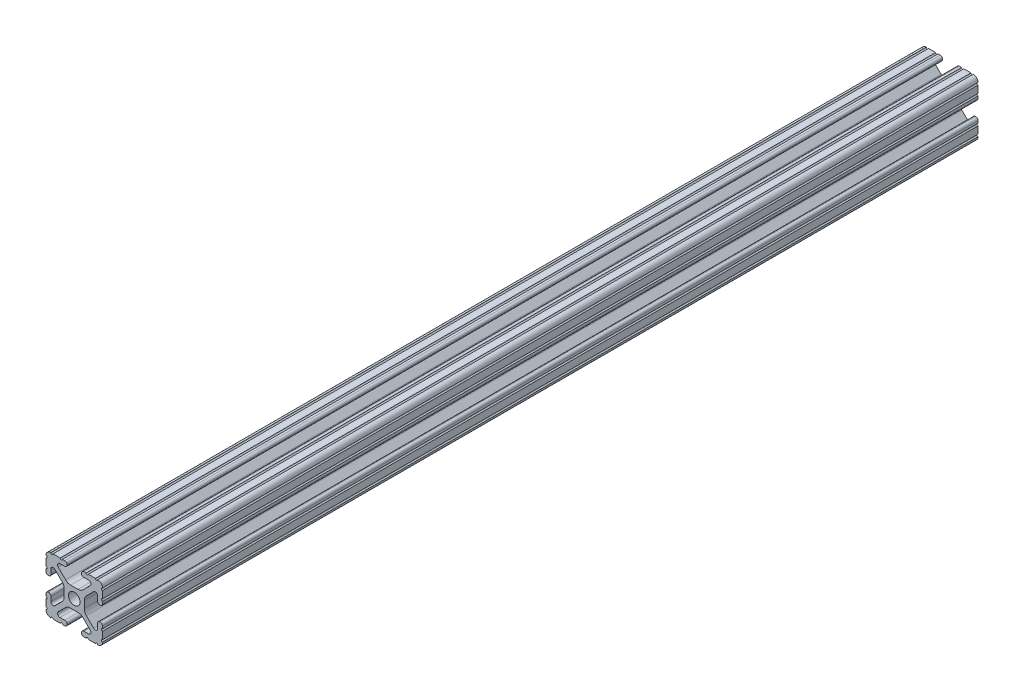
SolidWorks part; units mm, degrees
ref_plane "Front Plane" through (0, 0, 0) normal (0, 0, 1) x (1, 0, 0)
ref_plane "Top Plane" through (0, 0, 0) normal (0, 1, 0) x (1, 0, 0)
ref_plane "Right Plane" through (0, 0, 0) normal (1, 0, 0) x (0, 0, -1)
sketch "Sketch1" plane through (0, 0, 0) normal (0, 0, 1) x (1, 0, 0)
  line L88 (-7.1797, -8.6452) -> (-3.9523, -5.4237)
  line L89 (-1.7093, -4.4958) -> (1.7093, -4.4958)
  line L90 (3.9523, -5.4237) -> (7.1797, -8.6452)
  line L91 (6.4164, -10.4902) -> (4.2875, -10.4902)
  line L92 (3.2385, -11.5392) -> (3.2385, -11.651)
  line L93 (4.2875, -12.7) -> (5.3171, -12.7)
  line L94 (6.3331, -12.7) -> (9.5504, -12.7)
  line L95 (12.7, -9.5504) -> (12.7, -6.3331)
  line L96 (12.7, -5.3171) -> (12.7, -4.2875)
  line L97 (11.651, -3.2385) -> (11.5392, -3.2385)
  line L98 (10.4902, -4.2875) -> (10.4902, -6.4021)
  line L99 (8.7371, -7.1294) -> (5.441, -3.8408)
  line L100 (4.5085, -1.5932) -> (4.5085, 1.5932)
  line L101 (5.441, 3.8408) -> (8.7371, 7.1294)
  line L102 (10.4902, 6.4021) -> (10.4902, 4.2875)
  line L103 (11.5392, 3.2385) -> (11.651, 3.2385)
  line L104 (12.7, 4.2875) -> (12.7, 5.3171)
  line L105 (12.7, 6.3331) -> (12.7, 9.5504)
  line L106 (9.5504, 12.7) -> (6.3331, 12.7)
  line L107 (5.3171, 12.7) -> (4.2875, 12.7)
  line L108 (3.2385, 11.651) -> (3.2385, 11.5392)
  line L109 (4.2875, 10.4902) -> (6.4768, 10.4902)
  line L110 (7.207, 8.7244) -> (3.8983, 5.4232)
  line L111 (1.6558, 4.4958) -> (-1.6558, 4.4958)
  line L112 (-3.8983, 5.4232) -> (-7.207, 8.7244)
  line L113 (-6.4768, 10.4902) -> (-4.2875, 10.4902)
  line L114 (-3.2385, 11.5392) -> (-3.2385, 11.651)
  line L115 (-4.2875, 12.7) -> (-5.3171, 12.7)
  line L116 (-6.3331, 12.7) -> (-9.5504, 12.7)
  line L117 (-12.7, 9.5504) -> (-12.7, 6.3331)
  line L118 (-12.7, 5.3171) -> (-12.7, 4.2875)
  line L119 (-11.651, 3.2385) -> (-11.5392, 3.2385)
  line L120 (-10.4902, 4.2875) -> (-10.4902, 6.4021)
  line L121 (-8.7371, 7.1294) -> (-5.441, 3.8408)
  line L122 (-4.5085, 1.5932) -> (-4.5085, -1.5932)
  line L123 (-5.441, -3.8408) -> (-8.7371, -7.1294)
  line L124 (-10.4902, -6.4021) -> (-10.4902, -4.2875)
  line L125 (-11.5392, -3.2385) -> (-11.651, -3.2385)
  line L126 (-12.7, -4.2875) -> (-12.7, -5.3171)
  line L127 (-12.7, -6.3331) -> (-12.7, -9.5504)
  line L128 (-9.5504, -12.7) -> (-6.3331, -12.7)
  line L129 (-5.3171, -12.7) -> (-4.2875, -12.7)
  line L130 (-3.2385, -11.651) -> (-3.2385, -11.5392)
  line L131 (-4.2875, -10.4902) -> (-6.4164, -10.4902)
  circle A1 centre (0, 0) radius 2.6035
  arc A104 (-7.1797, -8.6452) -> (-6.4164, -10.4902) centre (-6.4164, -9.4098) ccw
  arc A105 (-1.7093, -4.4958) -> (-3.9523, -5.4237) centre (-1.7093, -7.6708) ccw
  arc A106 (3.9523, -5.4237) -> (1.7093, -4.4958) centre (1.7093, -7.6708) ccw
  arc A107 (6.4164, -10.4902) -> (7.1797, -8.6452) centre (6.4164, -9.4098) ccw
  arc A108 (4.2875, -10.4902) -> (3.2385, -11.5392) centre (4.2875, -11.5392) ccw
  arc A109 (3.2385, -11.651) -> (4.2875, -12.7) centre (4.2875, -11.651) ccw
  arc A110 (6.3331, -12.7) -> (5.3171, -12.7) centre (5.8251, -12.7) ccw
  arc A111 (10.5664, -12.6998) -> (9.5504, -12.7) centre (10.0584, -12.7) ccw
  arc A112 (10.5664, -12.6998) -> (12.6998, -10.5664) centre (10.5918, -10.5918) ccw
  arc A113 (12.7, -9.5504) -> (12.6998, -10.5664) centre (12.7, -10.0584) ccw
  arc A114 (12.7, -5.3171) -> (12.7, -6.3331) centre (12.7, -5.8251) ccw
  arc A115 (12.7, -4.2875) -> (11.651, -3.2385) centre (11.651, -4.2875) ccw
  arc A116 (11.5392, -3.2385) -> (10.4902, -4.2875) centre (11.5392, -4.2875) ccw
  arc A117 (8.7371, -7.1294) -> (10.4902, -6.4021) centre (9.4628, -6.4021) ccw
  arc A118 (4.5085, -1.5932) -> (5.441, -3.8408) centre (7.6835, -1.5932) ccw
  arc A119 (5.441, 3.8408) -> (4.5085, 1.5932) centre (7.6835, 1.5932) ccw
  arc A120 (10.4902, 6.4021) -> (8.7371, 7.1294) centre (9.4628, 6.4021) ccw
  arc A121 (10.4902, 4.2875) -> (11.5392, 3.2385) centre (11.5392, 4.2875) ccw
  arc A122 (11.651, 3.2385) -> (12.7, 4.2875) centre (11.651, 4.2875) ccw
  arc A123 (12.7, 6.3331) -> (12.7, 5.3171) centre (12.7, 5.8251) ccw
  arc A124 (12.6998, 10.5664) -> (12.7, 9.5504) centre (12.7, 10.0584) ccw
  arc A125 (12.6998, 10.5664) -> (10.5664, 12.6998) centre (10.5918, 10.5918) ccw
  arc A126 (9.5504, 12.7) -> (10.5664, 12.6998) centre (10.0584, 12.7) ccw
  arc A127 (5.3171, 12.7) -> (6.3331, 12.7) centre (5.8251, 12.7) ccw
  arc A128 (4.2875, 12.7) -> (3.2385, 11.651) centre (4.2875, 11.651) ccw
  arc A129 (3.2385, 11.5392) -> (4.2875, 10.4902) centre (4.2875, 11.5392) ccw
  arc A130 (7.207, 8.7244) -> (6.4768, 10.4902) centre (6.4768, 9.4563) ccw
  arc A131 (1.6558, 4.4958) -> (3.8983, 5.4232) centre (1.6558, 7.6708) ccw
  arc A132 (-3.8983, 5.4232) -> (-1.6558, 4.4958) centre (-1.6558, 7.6708) ccw
  arc A133 (-6.4768, 10.4902) -> (-7.207, 8.7244) centre (-6.4768, 9.4563) ccw
  arc A134 (-4.2875, 10.4902) -> (-3.2385, 11.5392) centre (-4.2875, 11.5392) ccw
  arc A135 (-3.2385, 11.651) -> (-4.2875, 12.7) centre (-4.2875, 11.651) ccw
  arc A136 (-6.3331, 12.7) -> (-5.3171, 12.7) centre (-5.8251, 12.7) ccw
  arc A137 (-10.5664, 12.6998) -> (-9.5504, 12.7) centre (-10.0584, 12.7) ccw
  arc A138 (-10.5664, 12.6998) -> (-12.6998, 10.5664) centre (-10.5918, 10.5918) ccw
  arc A139 (-12.7, 9.5504) -> (-12.6998, 10.5664) centre (-12.7, 10.0584) ccw
  arc A140 (-12.7, 5.3171) -> (-12.7, 6.3331) centre (-12.7, 5.8251) ccw
  arc A141 (-12.7, 4.2875) -> (-11.651, 3.2385) centre (-11.651, 4.2875) ccw
  arc A142 (-11.5392, 3.2385) -> (-10.4902, 4.2875) centre (-11.5392, 4.2875) ccw
  arc A143 (-8.7371, 7.1294) -> (-10.4902, 6.4021) centre (-9.4628, 6.4021) ccw
  arc A144 (-4.5085, 1.5932) -> (-5.441, 3.8408) centre (-7.6835, 1.5932) ccw
  arc A145 (-5.441, -3.8408) -> (-4.5085, -1.5932) centre (-7.6835, -1.5932) ccw
  arc A146 (-10.4902, -6.4021) -> (-8.7371, -7.1294) centre (-9.4628, -6.4021) ccw
  arc A147 (-10.4902, -4.2875) -> (-11.5392, -3.2385) centre (-11.5392, -4.2875) ccw
  arc A148 (-11.651, -3.2385) -> (-12.7, -4.2875) centre (-11.651, -4.2875) ccw
  arc A149 (-12.7, -6.3331) -> (-12.7, -5.3171) centre (-12.7, -5.8251) ccw
  arc A150 (-12.6998, -10.5664) -> (-12.7, -9.5504) centre (-12.7, -10.0584) ccw
  arc A151 (-12.6998, -10.5664) -> (-10.5664, -12.6998) centre (-10.5918, -10.5918) ccw
  arc A152 (-9.5504, -12.7) -> (-10.5664, -12.6998) centre (-10.0584, -12.7) ccw
  arc A153 (-5.3171, -12.7) -> (-6.3331, -12.7) centre (-5.8251, -12.7) ccw
  arc A154 (-4.2875, -12.7) -> (-3.2385, -11.651) centre (-4.2875, -11.651) ccw
  arc A155 (-3.2385, -11.5392) -> (-4.2875, -10.4902) centre (-4.2875, -11.5392) ccw
extrude "Boss-Extrude1" add sketch "Sketch1" along normal mid plane 609.6
sketch "Sketch4" plane through (0, 0, 304.8) normal (0, 0, 1) x (1, 0, 0)
  line L1 (-53.9077, 39.7643) -> (57.9736, 39.7643)
  line L2 (-53.9077, 39.7643) -> (-53.9077, -54.0624)
  line L3 (-53.9077, -54.0624) -> (57.9736, -54.0624)
  line L4 (57.9736, 39.7643) -> (57.9736, -54.0624)
extrude "Cut-Extrude3" cut sketch "Sketch4" against normal blind 215.9
